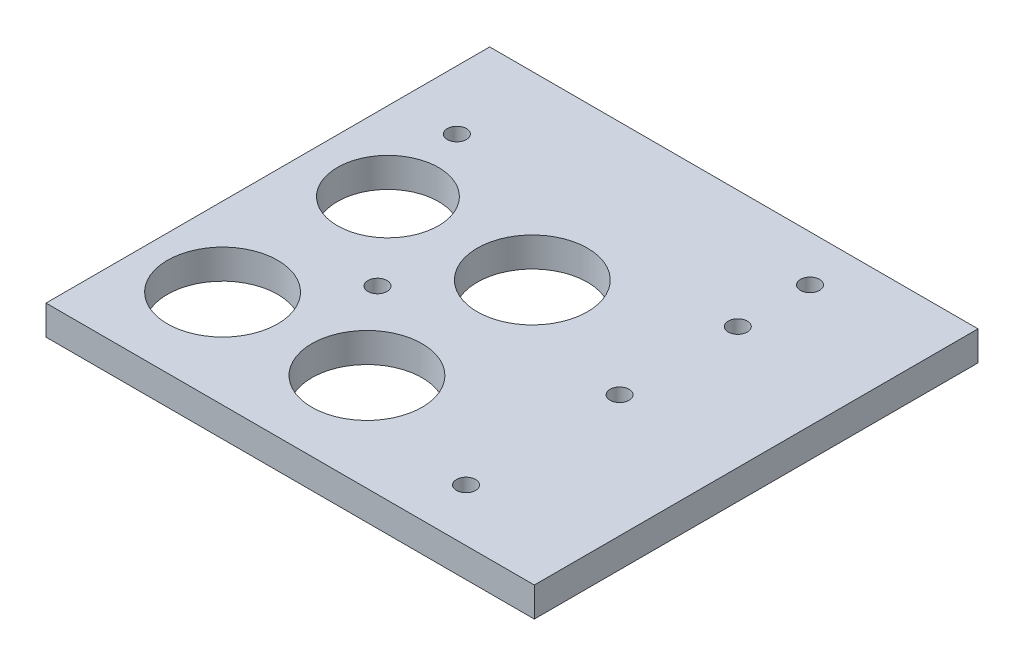
SolidWorks part; units mm, degrees
ref_plane "Front Plane" through (0, 0, 0) normal (0, 0, 1) x (1, 0, 0)
ref_plane "Top Plane" through (0, 0, 0) normal (0, 1, 0) x (1, 0, 0)
ref_plane "Right Plane" through (0, 0, 0) normal (1, 0, 0) x (0, 0, -1)
sketch "Sketch1" plane through (0, 0, 0) normal (0, 1, 0) x (1, 0, 0)
  line L1 (-29.21, 50.927) -> (65.278, 50.927)
  line L2 (-29.21, 50.927) -> (-29.21, -34.925)
  line L3 (-29.21, -34.925) -> (65.278, -34.925)
  line L4 (65.278, 50.927) -> (65.278, -34.925)
  circle A0 centre (-13.97, 16.002) radius 9.779
  circle A1 centre (13.97, 16.002) radius 10.668
  circle A2 centre (13.97, -16.002) radius 10.668
  circle A3 centre (-13.97, -16.002) radius 10.668
  point P0 (0, 0)
  dimension "D5" = 19.558
  dimension "D6" = 18.923
  dimension "D7" = 50.927
  dimension "D1" = 85.852
  dimension "D2" = 65.278
  dimension "D3" = 29.21
  dimension "D4" = 34.925
extrude "Boss-Extrude1" add sketch "Sketch1" along normal blind 5.715
sketch "Sketch3" plane through (0, 5.715, 0) normal (0, 1, 0) x (1, 0, 0)
  line L0 (65.278, -34.925) -> (65.278, 50.927) construction
  line L1 (65.278, 50.927) -> (-29.21, 50.927) construction
  line L2 (-29.21, -34.925) -> (65.278, -34.925) construction
  circle A0 centre (41.656, 42.037) radius 2.54
  circle A1 centre (41.91, -24.765) radius 2.54
  circle A2 centre (0, 0) radius 3.4977
  circle A3 centre (-17.78, 33.147) radius 2.5302
  circle A5 centre (41.656, 5.207) radius 3.0354
  circle A6 centre (41.656, 28.067) radius 2.0783
  dimension "D3" = 23.368
  dimension "D4" = 8.89
  dimension "D6" = 65.278
  dimension "D7" = 5.08
  dimension "D8" = 5.08
  dimension "D9" = 50.927
  dimension "D10" = 22.86
  dimension "D13" = 23.622
  dimension "D14" = 45.72
  dimension "D2" = 23.622
  dimension "D5" = 10.16
  dimension "D12" = 17.78
  dimension "D15" = 23.622
  dimension "D16" = 83.058
hole_wizard "M3 Clearance Hole1" positions "Sketch4" profile "Sketch5" hole size "M3" standard "ANSI Metric"
sketch "Sketch4" plane through (0, 5.715, 0) normal (0, 1, 0) x (1, 0, 0)
  point P0 (41.656, 42.037)
  point P3 (41.91, -24.765)
  point P9 (-17.78, 33.147)
  point P12 (41.656, 5.207)
  point P18 (41.656, 28.067)
  point P23 (0, 0)
sketch "Sketch5" plane through (41.656, 5.715, -42.037) normal (1, 0, 0) x (0, 0, 1)
  line L0 (0, 0) -> (0, 26.5116)
  line L1 (0, 26.5116) -> (1.85, 25.4)
  line L2 (1.85, 25.4) -> (1.85, 0)
  line L5 (1.85, 0) -> (0, 0)
  line L10 (0, 26.5116) -> (-1.85, 25.4) construction
  line L11 (0, -6.35) -> (0, 107.95) construction
  dimension "Hole Dia." = 3.7
  dimension "Hole Depth" = 25.4
  dimension "Drill Angle" = 118
